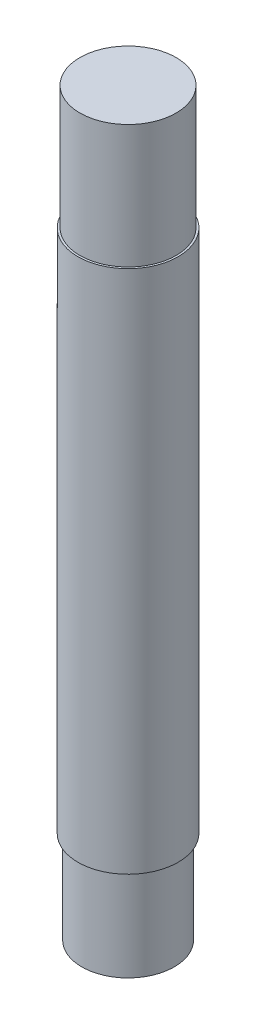
SolidWorks part; units mm, degrees
material "PUR"
ref_plane "Z" through (0, 0, 0) normal (0, 0, 1) x (1, 0, 0)
ref_plane "Y" through (0, 0, 0) normal (0, 1, 0) x (1, 0, 0)
ref_plane "X" through (0, 0, 0) normal (1, 0, 0) x (0, 0, -1)
sketch "Sketch1" plane through (0, 0, 0) normal (0, 1, 0) x (1, 0, 0)
  circle A0 centre (0, 0) radius 5.1594
  dimension "D1" = 10.3187
extrude "Boss-Extrude1" add sketch "Sketch1" along normal blind 76.2
sketch "Sketch2" plane through (0, 76.2, 0) normal (0, 1, 0) x (1, 0, 0)
  circle A0 centre (0, 0) radius 4.95
  circle A1 centre (0, 0) radius 5.5825
  dimension "D1" = 9.9
extrude "Cut-Extrude1" cut sketch "Sketch2" against normal blind 12.7
sketch "Sketch4" plane through (4747.8489, 34.4731, 51.9152) normal (0, -1, 0) x (-1, 0, 0)
  line L0 (4747.8489, 57.1152) -> (4747.8489, 56.4802) construction
  line L1 (4747.8489, 49.4072) -> (4747.8489, 128.9496) construction
  line L2 (4747.8489, 56.4802) -> (4739.6723, 56.4802)
  line L3 (4739.6723, 56.4802) -> (4739.6723, 59.6804)
  line L4 (4739.6723, 59.6804) -> (4755.9432, 59.6804)
  line L5 (4755.9432, 59.6804) -> (4755.9432, 56.4802)
  line L6 (4755.9432, 56.4802) -> (4747.8489, 56.4802)
  circle A0 centre (4747.8489, 51.9152) radius 5.2 construction
  dimension "D1" = 0.635
extrude "Cut-Extrude2" cut sketch "Sketch4" against normal blind 15.24
sketch "Sketch5" plane through (0, 0, 0) normal (0, -1, 0) x (1, 0, 0)
  circle A0 centre (0, 0) radius 4.7625
  circle A1 centre (0, 0) radius 6.8554
  dimension "D1" = 9.525
extrude "Cut-Extrude3" cut sketch "Sketch5" against normal blind 9.525
